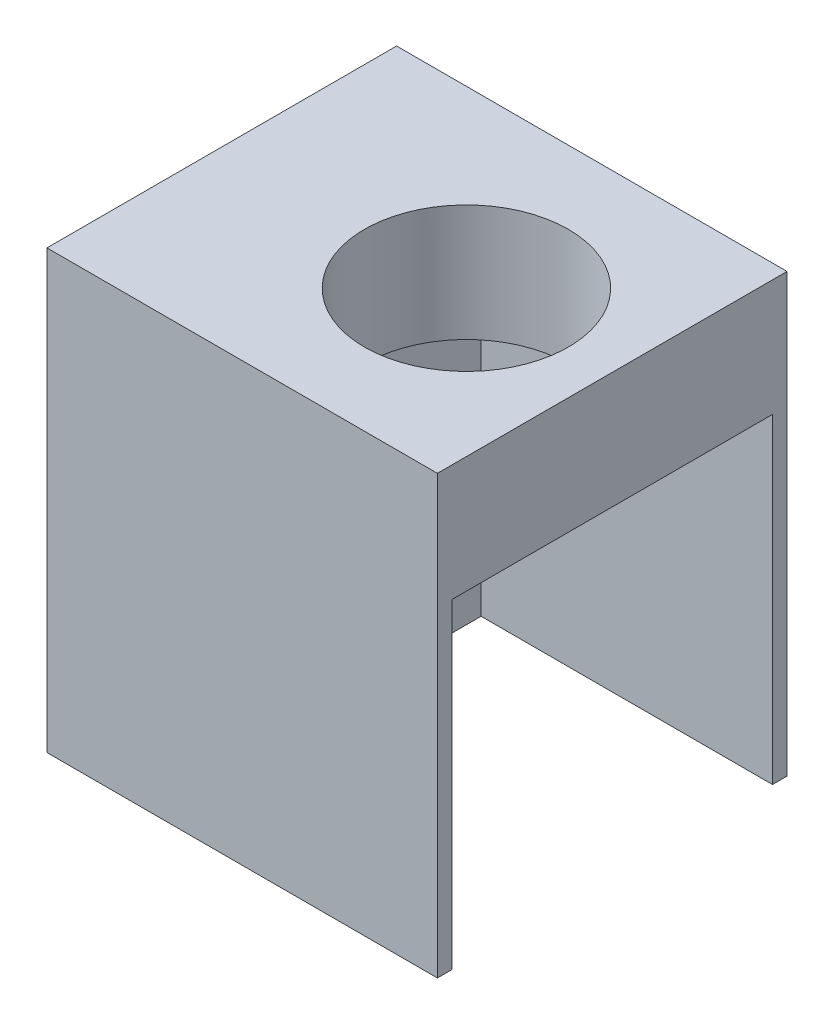
SolidWorks part; units mm, degrees
ref_plane "前视基准面" through (0, 0, 0) normal (0, 0, 1) x (1, 0, 0)
ref_plane "上视基准面" through (0, 0, 0) normal (0, 1, 0) x (1, 0, 0)
ref_plane "右视基准面" through (0, 0, 0) normal (1, 0, 0) x (0, 0, -1)
other "Configuration Table"
sketch "草图2" plane through (0, 0, 0) normal (0, 1, 0) x (1, 0, 0)
  line L1 (13.4, 0) -> (0, 0)
  line L2 (13.4, 0) -> (13.4, -12)
  line L3 (13.4, -12) -> (0, -12)
  line L4 (0, 0) -> (0, -12)
  circle A0 centre (8.3957, -6) radius 3.5
  dimension "D3" = 7
  dimension "D1" = 12
  dimension "D2" = 13.4
extrude "凸台-拉伸2" add sketch "草图2" along normal blind 15 contours L1 L4 L3 L2 | A0
sketch "草图3" plane through (0, 0, 0) normal (0, -1, 0) x (1, 0, 0)
  line L1 (13.4, 11.5) -> (3.4, 11.5)
  line L2 (13.4, 11.5) -> (13.4, 0.5)
  line L3 (13.4, 0.5) -> (3.4, 0.5)
  line L4 (3.4, 11.5) -> (3.4, 0.5)
  line L5 (0, 6) -> (13.4, 6) construction
  line L6 (0, 0) -> (0, 12) construction
  line L7 (13.4, 0) -> (13.4, 12) construction
  point P9 (3.4, 6)
  dimension "D1" = 10
  dimension "D2" = 11
extrude "切除-拉伸1" cut sketch "草图3" against normal offset from surface (11 mm away) 4 up to face at (6.7, 15, 6)
